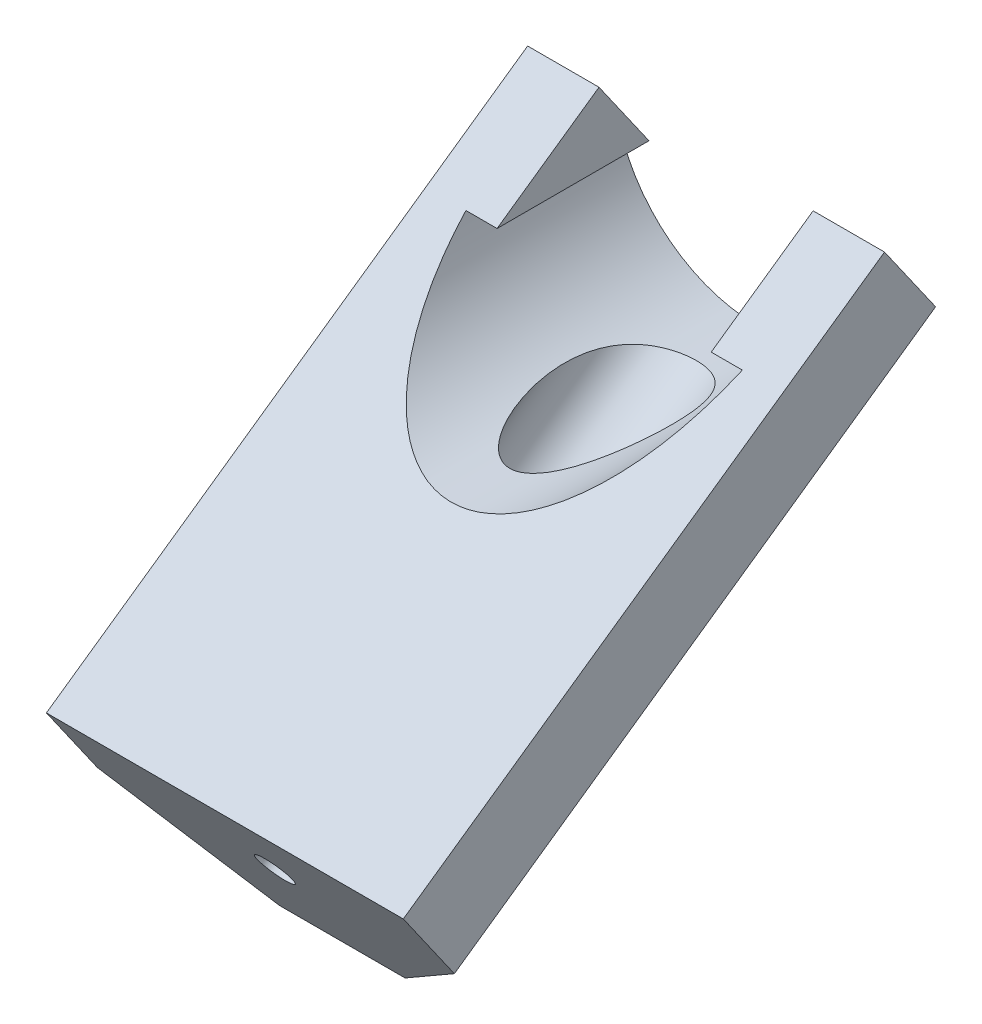
SolidWorks part; units mm, degrees
ref_plane "Front Plane" through (0, 0, 0) normal (0, 0, 1) x (1, 0, 0)
ref_plane "Top Plane" through (0, 0, 0) normal (0, 1, 0) x (1, 0, 0)
ref_plane "Right Plane" through (0, 0, 0) normal (1, 0, 0) x (0, 0, -1)
sketch "Sketch1" plane through (0, 0, 0) normal (0, 0, 1) x (1, 0, 0)
  line L0 (-20, 0) -> (20, 0) construction
  line L1 (-15, 0) -> (-15, 5)
  line L2 (-15, 5) -> (-25, 5)
  line L3 (-25, 5) -> (-25, -25)
  line L4 (-25, -25) -> (25, -25)
  line L5 (25, -25) -> (25, 5)
  line L6 (25, 5) -> (15, 5)
  line L7 (15, 5) -> (15, -5)
  line L8 (15, -5) -> (19.3649, -5)
  line L9 (-15, 0) -> (-15, -5)
  line L10 (-15, -5) -> (-19.3649, -5)
  line L11 (0, -20) -> (0, -25) construction
  arc A0 (-19.3649, -5) -> (19.3649, -5) centre (0, 0) ccw
  dimension "D1" = 40
  dimension "D2" = 5
  dimension "D3" = 5
  dimension "D4" = 5
  dimension "D5" = 5
  dimension "D6" = 5
  dimension "D7" = 10
  dimension "D8" = 5
  dimension "D9" = 5
  dimension "D10" = 5
  dimension "D11" = 40
extrude "Boss-Extrude1" add sketch "Sketch1" along normal blind 50
sketch "Sketch2" plane through (25, 0, 0) normal (1, 0, 0) x (0, 0, -1)
  line L0 (-50, -25) -> (-7.1556, 5) construction
  line L1 (-50, 5) -> (0, 5) construction
  line L2 (-7.1556, 5) -> (9.2939, -18.4923) construction
  line L3 (-50, -25) -> (-33.5505, -48.4923) construction
  line L4 (-33.5505, -48.4923) -> (9.2939, -18.4923) construction
  line L5 (-50, -25) -> (-50, 5)
  line L7 (-7.1556, 5) -> (42.8444, 5)
  line L8 (9.2939, -18.4923) -> (42.8444, 5)
  line L10 (0, -5.2192) -> (0, 5)
  line L11 (-50, 5) -> (-7.1556, 5)
  line L12 (0, 5) -> (-7.1556, 5)
  line L13 (-50, -25) -> (-7.1556, 5)
  line L14 (-7.1556, 5) -> (0, -5.2192)
  dimension "D1" = 90
  dimension "D2" = 90
  dimension "D3" = 35
  dimension "D5" = 0
extrude "Cut-Extrude1" cut sketch "Sketch2" against normal through all contours L11 L5 L13 | L14 L10 L12
sketch "Sketch4" plane through (0, -1.7171, 2.4522) normal (0, 0.5736, -0.8192) x (-1, 0, 0)
  line L0 (-25, -4.2753) -> (0, -29.2753)
  line L1 (0, -29.2753) -> (25, -4.2753)
  line L2 (0, 0) -> (0, -29.2753) construction
  line L3 (-25, -4.2753) -> (-25, -29.2753)
  line L4 (-25, -29.2753) -> (0, -29.2753)
  line L5 (25, -4.2753) -> (25, -29.2753)
  line L6 (25, -29.2753) -> (0, -29.2753)
  dimension "D1" = 90
extrude "Cut-Extrude2" cut sketch "Sketch4" against normal through all contours L0 L3 L4 | L1 L5 L6
sketch "Sketch6" plane through (25, 0, 0) normal (1, 0, 0) x (0, 0, -1)
  line L0 (-50, -25) -> (-74.5746, -42.2073)
  line L1 (-74.5746, -42.2073) -> (-58.1251, -65.6996)
  line L2 (-58.1251, -65.6996) -> (0, -25)
  line L3 (-50, -25) -> (-7.1556, 5) construction
  line L4 (0, -25) -> (-50, -25)
  dimension "D1" = 90
  dimension "D2" = 30
extrude "Boss-Extrude2" add sketch "Sketch6" against normal up to surface (50 mm away) up to face at (-25, -12.5548, 21.3514)
sketch "Sketch7" plane through (0, -1.7171, 2.4522) normal (0, 0.5736, -0.8192) x (-1, 0, 0)
  line L0 (25, -4.2753) -> (25, -20.4788)
  line L1 (25, -20.4788) -> (8.7965, -20.4788)
  line L2 (8.7965, -20.4788) -> (25, -4.2753)
  line L3 (-25, -4.2753) -> (-8.7965, -20.4788)
  line L4 (-8.7965, -20.4788) -> (-25, -20.4788)
  line L5 (-25, -20.4788) -> (-25, -4.2753)
extrude "Cut-Extrude3" cut sketch "Sketch7" against normal through all
sketch "Sketch8" plane through (0, -1.7171, 2.4522) normal (0, 0.5736, -0.8192) x (-1, 0, 0)
  line L0 (-15, -4.0077) -> (15, -4.0077) construction
  circle A0 centre (0, -4.0077) radius 2.5
  dimension "D1" = 5
extrude "Cut-Extrude4" cut sketch "Sketch8" against normal through all contours A0
sketch "Sketch9" plane through (0, -1.7171, 2.4522) normal (0, 0.5736, -0.8192) x (-1, 0, 0)
  circle A0 centre (0, -4.0077) radius 7.5
  dimension "D1" = 15
extrude "Cut-Extrude5" cut sketch "Sketch9" against normal blind 40
